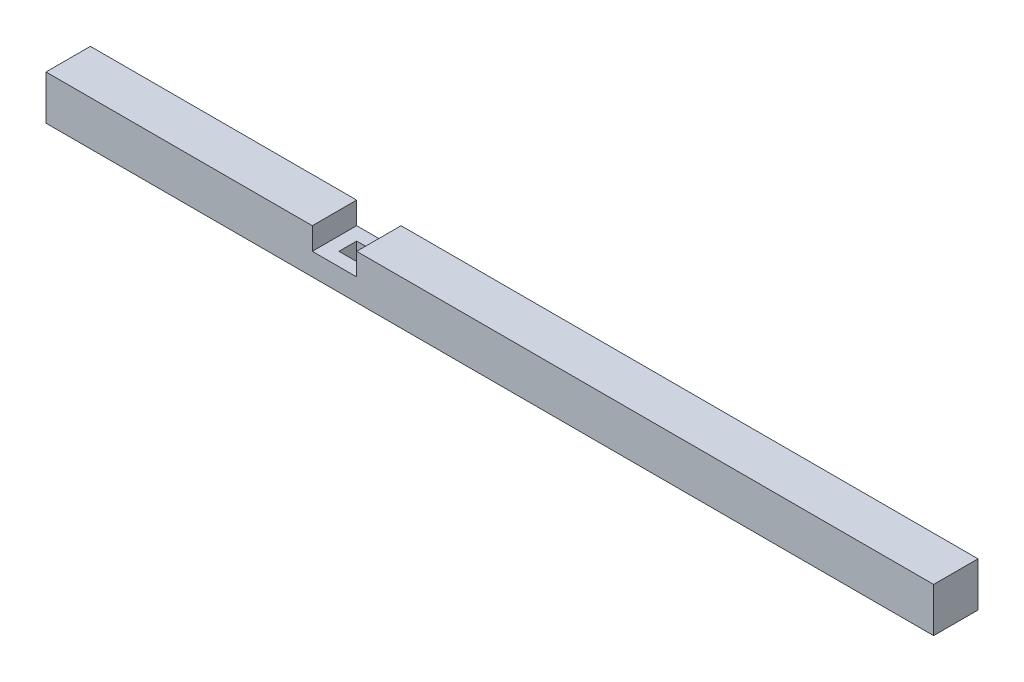
SolidWorks part; units mm, degrees
material "Balsa"
ref_plane "Plan de face" through (0, 0, 0) normal (0, 0, 1) x (1, 0, 0)
ref_plane "Plan de dessus" through (0, 0, 0) normal (0, 1, 0) x (1, 0, 0)
ref_plane "Plan de droite" through (0, 0, 0) normal (1, 0, 0) x (0, 0, -1)
sketch "Sketch1" plane through (0, 0, 0) normal (1, 0, 0) x (0, 0, -1)
  line L1 (0, 0) -> (25, 0)
  line L2 (0, 0) -> (0, 25)
  line L3 (0, 25) -> (25, 25)
  line L4 (25, 0) -> (25, 25)
  dimension "D1" = 25
  dimension "D2" = 25
extrude "Boss-Extrude1" add sketch "Sketch1" along normal blind 500
sketch "Sketch2" plane through (0, 0, 0) normal (0, 0, 1) x (1, 0, 0)
  line L0 (500, 25) -> (0, 25) construction
  line L1 (150, 25) -> (175, 25)
  line L2 (150, 25) -> (150, 12.5)
  line L3 (150, 12.5) -> (175, 12.5)
  line L4 (175, 25) -> (175, 12.5)
  line L5 (0, 25) -> (0, 0) construction
  dimension "D1" = 25
  dimension "D2" = 12.5
  dimension "D3" = 150
extrude "Cut-Extrude1" cut sketch "Sketch2" against normal through all
sketch "Sketch3" plane through (0, 12.5, 0) normal (0, 1, 0) x (1, 0, 0)
  line L0 (150, 25) -> (175, 0) construction
  line L2 (157.5, 7.5) -> (167.5, 7.5)
  line L3 (157.5, 7.5) -> (157.5, 17.5)
  line L4 (157.5, 17.5) -> (167.5, 17.5)
  line L5 (167.5, 7.5) -> (167.5, 17.5)
  line L6 (157.5, 7.5) -> (167.5, 17.5) construction
  line L7 (157.5, 17.5) -> (167.5, 7.5) construction
  point P4 (162.5, 12.5)
  dimension "D1" = 10
extrude "Cut-Extrude2" cut sketch "Sketch3" against normal through all
